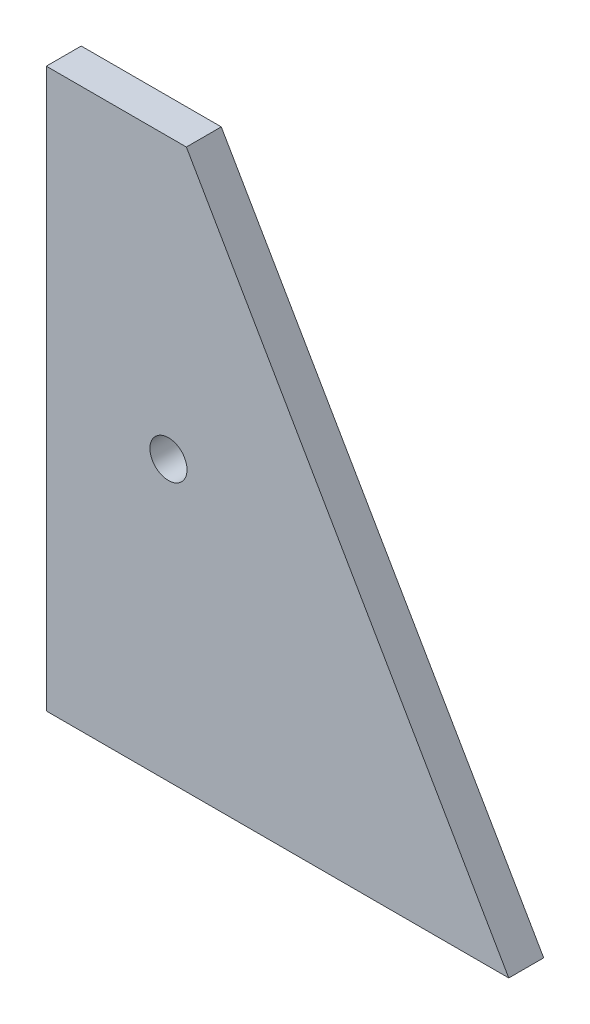
SolidWorks part; units mm, degrees
material "Pine"
ref_plane "Front Plane" through (0, 0, 0) normal (0, 0, 1) x (1, 0, 0)
ref_plane "Top Plane" through (0, 0, 0) normal (0, 1, 0) x (1, 0, 0)
ref_plane "Right Plane" through (0, 0, 0) normal (1, 0, 0) x (0, 0, -1)
sketch "Sketch1" plane through (0, 0, 0) normal (0, 0, 1) x (1, 0, 0)
  line L0 (0, 0) -> (0, 203.2)
  line L1 (0, 291.4608) -> (50.9574, 203.2) construction
  line L2 (168.275, 0) -> (0, 0)
  line L3 (50.9574, 203.2) -> (0, 203.2)
  line L4 (50.9574, 203.2) -> (168.275, 0)
  line L6 (0, 203.2) -> (0, 291.4608) construction
  dimension "D1" = 60
  dimension "D2" = 168.275
  dimension "D3" = 203.2
extrude "Boss-Extrude1" add sketch "Sketch1" along normal mid plane 12.7
hole_wizard "1/2 Clearance Hole1" positions "Sketch2" profile "Sketch3" hole size "1/2" standard "ANSI Inch" end condition through all
sketch "Sketch2" plane through (0, 0, 6.35) normal (0, 0, 1) x (1, 0, 0)
  line L0 (0, 0) -> (88.9, 0)
  line L1 (0, 0) -> (168.275, 0) construction
  line L3 (44.45, 0) -> (44.45, 203.2)
  line L5 (50.9574, 203.2) -> (0, 203.2) construction
  point P2 (44.45, 101.6)
  point P16 (44.45, 0)
  point P22 (0, 0)
  dimension "D1" = 88.9
  dimension "D2" = 101.6
sketch "Sketch3" plane through (44.45, 101.6, 6.35) normal (1, 0, 0) x (0, -1, 0)
  line L0 (0, 0) -> (0, 12.7)
  line L1 (0, 12.7) -> (6.7462, 12.7)
  line L2 (6.7462, 12.7) -> (6.7462, 0)
  line L5 (6.7462, 0) -> (0, 0)
  line L11 (0, -6.35) -> (0, 107.95) construction
  dimension "Thru Hole Dia." = 13.4925
  dimension "Thru Hole Depth" = 12.7
